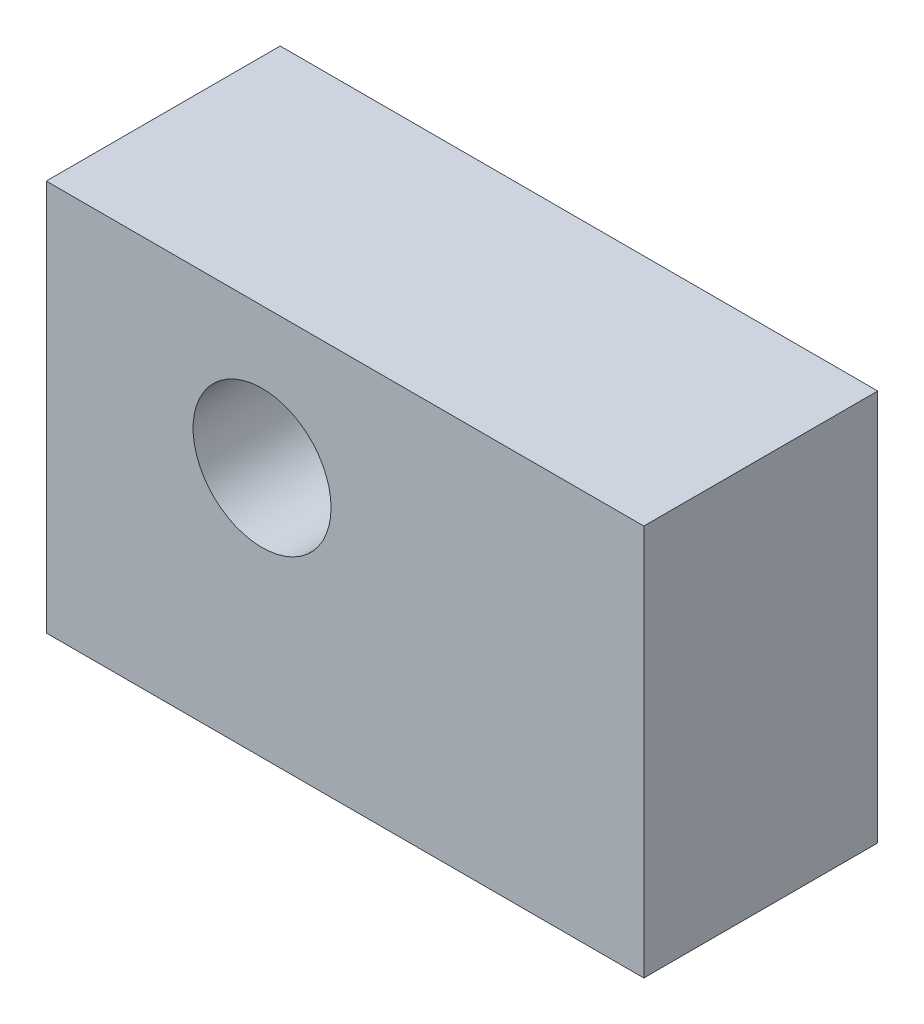
SolidWorks part; units mm, degrees
ref_plane "Front Plane" through (0, 0, 0) normal (0, 0, 1) x (1, 0, 0)
ref_plane "Top Plane" through (0, 0, 0) normal (0, 1, 0) x (1, 0, 0)
ref_plane "Right Plane" through (0, 0, 0) normal (1, 0, 0) x (0, 0, -1)
sketch "StockProfile" plane through (0, 0, 0) normal (0, 0, 1) x (1, 0, 0)
  line L1 (-32.48, -25.74) -> (38.82, -25.74)
  line L2 (-32.48, -25.74) -> (-32.48, 20.96)
  line L3 (-32.48, 20.96) -> (38.82, 20.96)
  line L4 (38.82, -25.74) -> (38.82, 20.96)
extrude "StockBoss" add sketch "StockProfile" along normal mid plane 27.91
sketch "ThroughProfile" plane through (0, 0, 0) normal (0, 0, 1) x (1, 0, 0)
  circle A0 centre (-6.73, 4.19) radius 8.23
extrude "ThroughFeature" cut sketch "ThroughProfile" along normal through all
